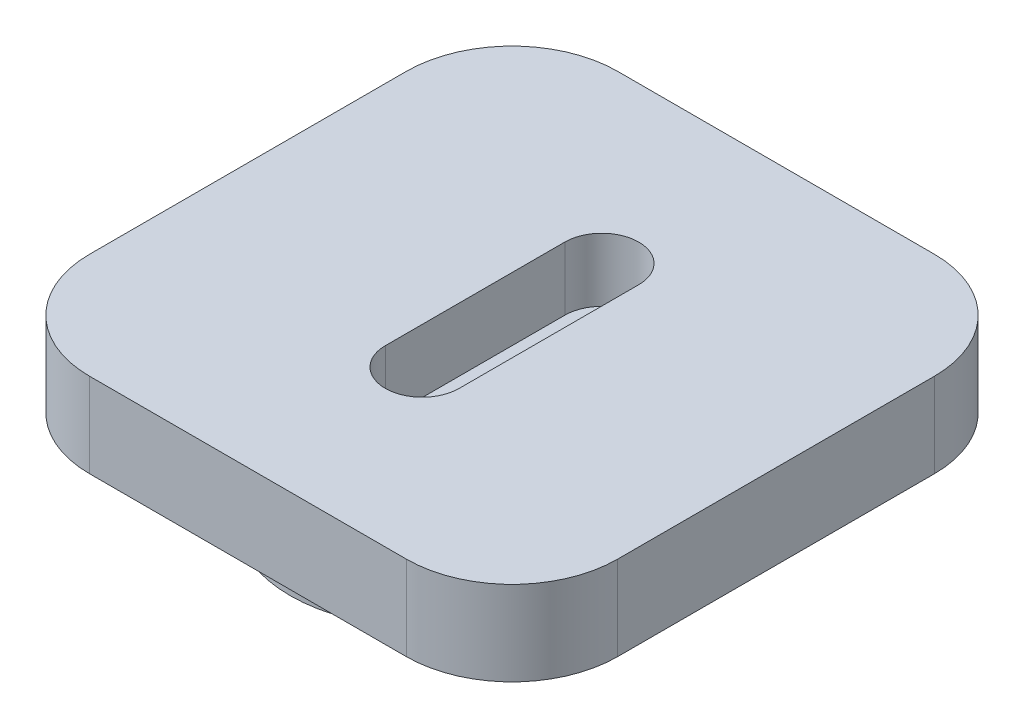
SolidWorks part; units mm, degrees
ref_plane "前视基准面" through (0, 0, 0) normal (0, 0, 1) x (1, 0, 0)
ref_plane "上视基准面" through (0, 0, 0) normal (0, 1, 0) x (1, 0, 0)
ref_plane "右视基准面" through (0, 0, 0) normal (1, 0, 0) x (0, 0, -1)
sketch "草图1" plane through (0, 0, 0) normal (0, 1, 0) x (1, 0, 0)
  line L0 (-23.4223, 0) -> (26.0794, 0) construction
  line L1 (0, 22.4873) -> (0, -17.9603) construction
  line L3 (-25, 25) -> (25, 25)
  line L4 (-25, 25) -> (-25, -25)
  line L5 (-25, -25) -> (25, -25)
  line L6 (25, 25) -> (25, -25)
  dimension "D1" = 50
extrude "凸台-拉伸1" add sketch "草图1" along normal blind 12.5
fillet "圆角1" radius 10 4 edges at (-25, 6.25, -25) (25, 6.25, -25) (-25, 6.25, 25) (25, 6.25, 25)
ref_plane "基准面2" through (0, 12.5, 0) normal (0, 1, 0) x (1, 0, 0)
sketch "草图2" plane through (0, 12.5, 0) normal (0, 1, 0) x (1, 0, 0)
  line L0 (0, 8.5) -> (0, -8.5) construction
  line L1 (3.5, 8.5) -> (3.5, -8.5)
  line L2 (-3.5, 8.5) -> (-3.5, -8.5)
  arc A0 (3.5, 8.5) -> (-3.5, 8.5) centre (0, 8.5) ccw
  arc A1 (-3.5, -8.5) -> (3.5, -8.5) centre (0, -8.5) ccw
  point P3 (0, 0)
  dimension "D1" = 17
  dimension "D2" = 3.5
extrude "切除-拉伸1" cut sketch "草图2" against normal blind 6
ref_plane "基准面3" through (0, 6.5, 0) normal (0, 1, 0) x (1, 0, 0)
sketch "草图3" plane through (0, 6.5, 0) normal (0, 1, 0) x (1, 0, 0)
  circle A0 centre (0, -8.5) radius 3.375
  arc A2 (-3.5, -8.5) -> (3.5, -8.5) centre (0, -8.5) ccw construction
  dimension "D1" = 6.75
  dimension "D2" = 0
extrude "切除-拉伸2" cut sketch "草图3" against normal blind 6
ref_plane "基准面4" through (0, 0, 0) normal (0, -1, 0) x (-1, 0, 0)
sketch "草图4" plane through (0, 0, 0) normal (0, -1, 0) x (-1, 0, 0)
  circle A0 centre (0, -8.5) radius 8.75
  circle A1 centre (0, -8.5) radius 3.375 construction
  dimension "D1" = 0
  dimension "D2" = 17.5
extrude "切除-拉伸3" cut sketch "草图4" against normal blind 3
ref_plane "基准面5" through (0, 0, 0) normal (0, -1, 0) x (-1, 0, 0)
sketch "草图5" plane through (0, 0, 0) normal (0, -1, 0) x (-1, 0, 0)
  line L1 (-32.6891, 29.5096) -> (35.0541, 29.5096)
  line L2 (-32.6891, 29.5096) -> (-32.6891, -29.6147)
  line L3 (-32.6891, -29.6147) -> (35.0541, -29.6147)
  line L4 (35.0541, 29.5096) -> (35.0541, -29.6147)
  circle A0 centre (0, -8.5) radius 12.5
  circle A1 centre (0, -8.5) radius 3.375 construction
  dimension "D1" = 25
extrude "切除-拉伸4" cut sketch "草图5" against normal blind 4.5 contours L4 L3 L2 L1 | A0
ref_plane "基准面6" through (0, 0, 0) normal (0, -1, 0) x (-1, 0, 0)
sketch "草图6" plane through (0, 0, 0) normal (0, -1, 0) x (-1, 0, 0)
  circle A0 centre (0, -8.5) radius 10.25
  circle A1 centre (0, -8.5) radius 11.25
  circle A2 centre (0, -8.5) radius 8.75 construction
  dimension "D1" = 1
  dimension "D2" = 1.5
extrude "切除-拉伸5" cut sketch "草图6" against normal blind 2
